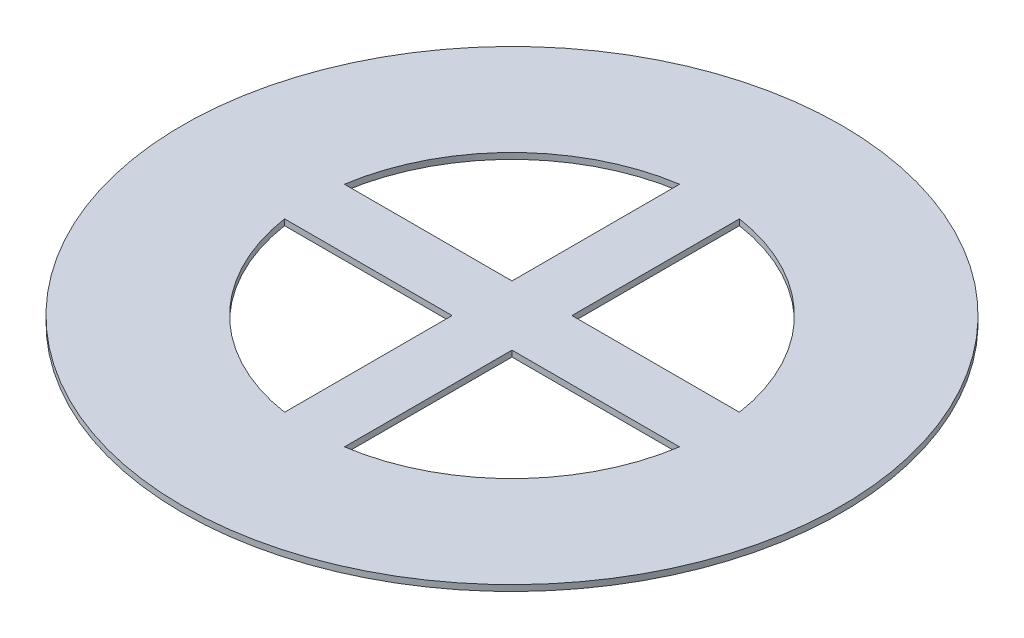
SolidWorks part; units mm, degrees
ref_plane "前视基准面" through (0, 0, 0) normal (0, 0, 1) x (1, 0, 0)
ref_plane "上视基准面" through (0, 0, 0) normal (0, 1, 0) x (1, 0, 0)
ref_plane "右视基准面" through (0, 0, 0) normal (1, 0, 0) x (0, 0, -1)
sketch "草图1" plane through (0, 0, 0) normal (0, 1, 0) x (1, 0, 0)
  line L0 (-15, 98.8686) -> (-15, 15)
  line L3 (15, 98.8686) -> (15, 15)
  line L4 (-98.8686, 15) -> (-15, 15)
  line L5 (-98.8686, -15) -> (-15, -15)
  line L6 (-15, -15) -> (-15, -98.8686)
  line L7 (15, 15) -> (98.8686, 15)
  line L8 (15, -15) -> (15, -98.8686)
  line L9 (15, -15) -> (98.8686, -15)
  circle A0 centre (0, 0) radius 165
  arc A1 (-98.8686, -15) -> (-15, -98.8686) centre (0, 0) ccw
  arc A2 (-15, 98.8686) -> (-98.8686, 15) centre (0, 0) ccw
  arc A3 (98.8686, 15) -> (15, 98.8686) centre (0, 0) ccw
  arc A4 (15, -98.8686) -> (98.8686, -15) centre (0, 0) ccw
  dimension "D1" = 330
  dimension "D2" = 200
  dimension "D3" = 30
  dimension "D4" = 30
  dimension "D5" = 15
  dimension "D6" = 15
extrude "凸台-拉伸1" add sketch "草图1" along normal blind 3
